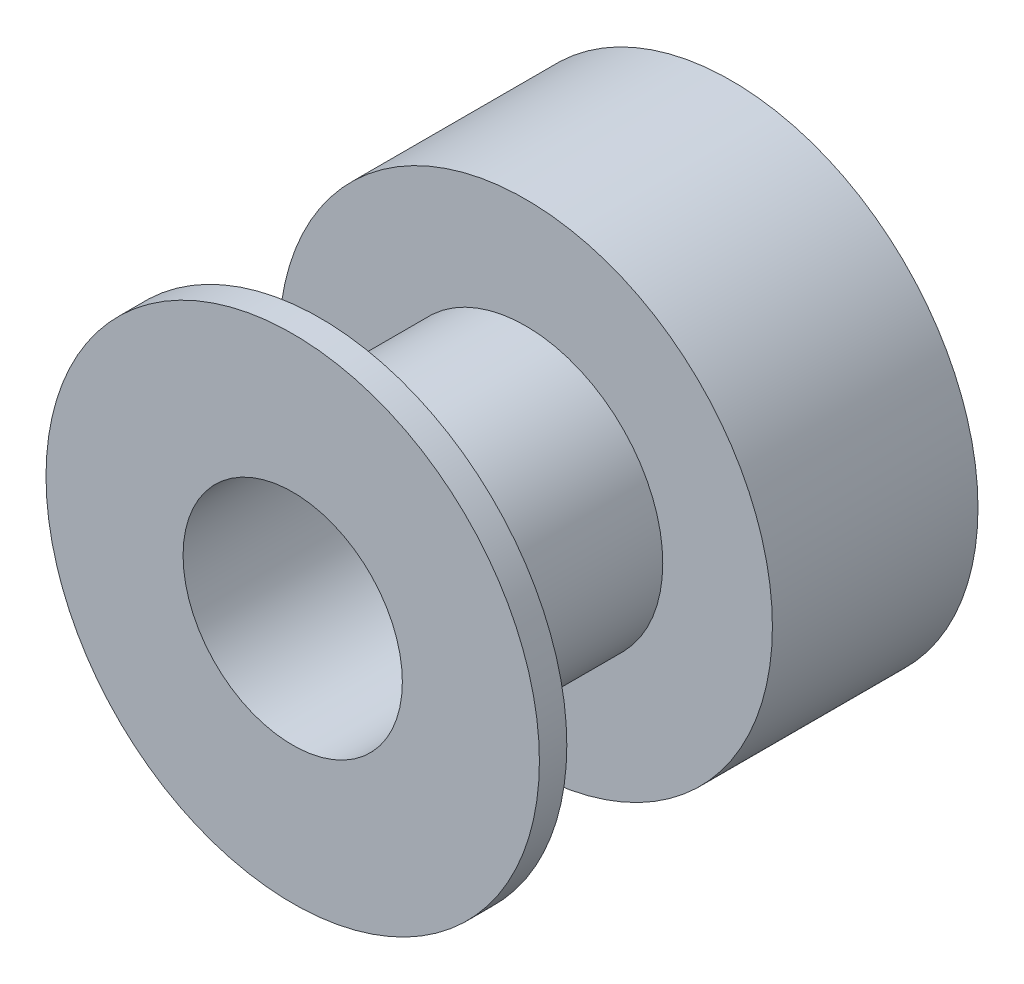
SolidWorks part; units mm, degrees
ref_plane "Front Plane" through (0, 0, 0) normal (0, 0, 1) x (1, 0, 0)
ref_plane "Top Plane" through (0, 0, 0) normal (0, 1, 0) x (1, 0, 0)
ref_plane "Right Plane" through (0, 0, 0) normal (1, 0, 0) x (0, 0, -1)
sketch "Sketch1" plane through (0, 0, 0) normal (0, 0, 1) x (1, 0, 0)
  circle A0 centre (0, 0) radius 9
  dimension "D1" = 18
extrude "Boss-Extrude1" add sketch "Sketch1" along normal blind 7.5
sketch "Sketch2" plane through (0, 0, 7.5) normal (0, 0, 1) x (1, 0, 0)
  circle A0 centre (0, 0) radius 5
  dimension "D1" = 10
extrude "Boss-Extrude2" add sketch "Sketch2" along normal blind 7.5
sketch "Sketch3" plane through (0, 0, 15) normal (0, 0, 1) x (1, 0, 0)
  circle A0 centre (0, 0) radius 9
  dimension "D1" = 18
extrude "Boss-Extrude3" add sketch "Sketch3" along normal blind 1
sketch "Sketch4" plane through (0, 0, 0) normal (0, 0, -1) x (-1, 0, 0)
  circle A0 centre (0, 0) radius 4
  dimension "D1" = 8
extrude "Cut-Extrude1" cut sketch "Sketch4" against normal blind 20
